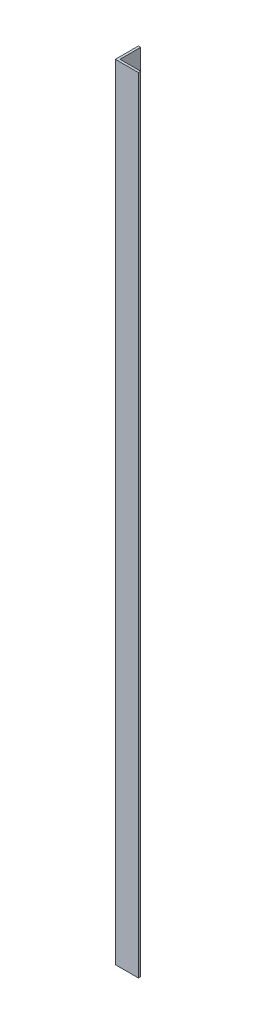
SolidWorks part; units mm, degrees
ref_plane "Front" through (0, 0, 0) normal (0, 0, 1) x (1, 0, 0)
ref_plane "Top" through (0, 0, 0) normal (0, 1, 0) x (1, 0, 0)
ref_plane "Right" through (0, 0, 0) normal (1, 0, 0) x (0, 0, -1)
sketch "Sketch1" plane through (0, 0, 0) normal (0, 1, 0) x (1, 0, 0)
  line L0 (0, 0) -> (0, 63.5)
  line L1 (0, 63.5) -> (6.35, 63.5)
  line L2 (6.35, 63.5) -> (6.35, 6.35)
  line L3 (6.35, 6.35) -> (63.5, 6.35)
  line L4 (63.5, 6.35) -> (63.5, 0)
  line L5 (63.5, 0) -> (0, 0)
  dimension "D1" = 63.5
  dimension "D2" = 6.35
extrude "Boss-Extrude1" add sketch "Sketch1" along normal blind 2165.35
sketch "Sketch2" [suppressed] plane through (0, 2165.35, 0) normal (0, 1, 0) x (1, 0, 0)
  line L6 (0, 0) -> (63.5, 0)
  line L7 (63.5, 0) -> (63.5, 6.35)
  line L8 (63.5, 6.35) -> (6.35, 6.35)
  line L9 (6.35, 6.35) -> (6.35, 63.5)
  line L10 (6.35, 63.5) -> (0, 63.5)
  line L11 (0, 63.5) -> (0, 0)
  line L12 (0, 0) -> (63.5, 0)
  line L13 (63.5, 0) -> (63.5, 6.35)
  line L14 (63.5, 6.35) -> (6.35, 6.35)
  line L15 (6.35, 6.35) -> (6.35, 63.5)
  line L16 (6.35, 63.5) -> (0, 63.5)
  line L17 (0, 63.5) -> (0, 0)
  dimension "D1" = 0
extrude "Boss-Extrude2" [suppressed] add sketch "Sketch2" along normal blind 146.05
